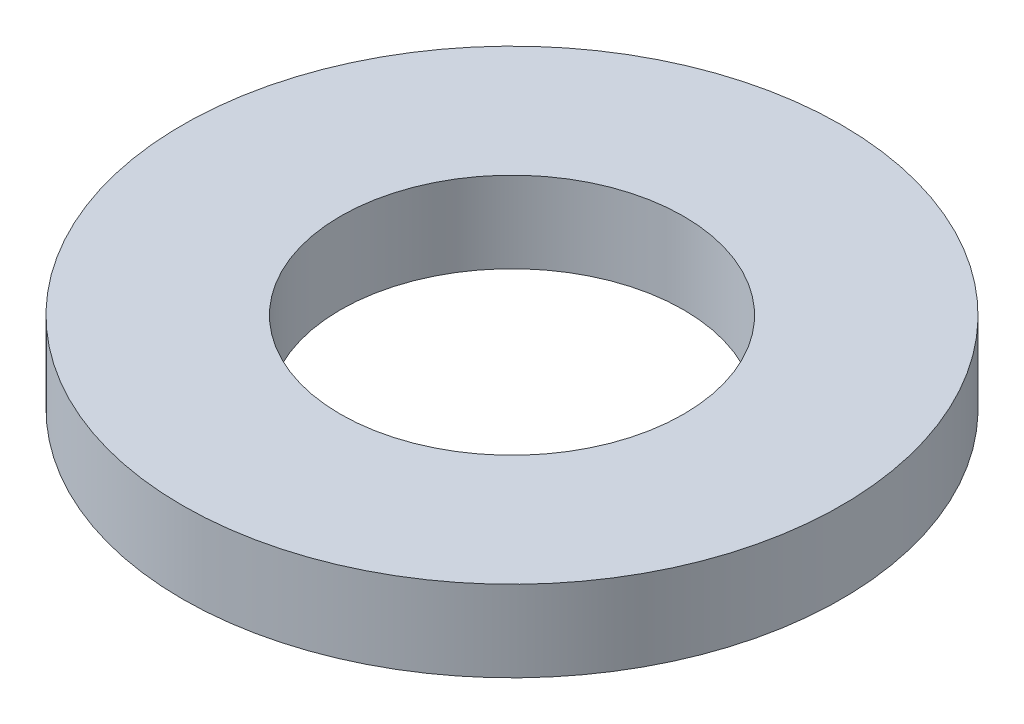
SolidWorks part; units mm, degrees
material "Alumina"
ref_plane "Front Plane" through (0, 0, 0) normal (0, 0, 1) x (1, 0, 0)
ref_plane "Top Plane" through (0, 0, 0) normal (0, 1, 0) x (1, 0, 0)
ref_plane "Right Plane" through (0, 0, 0) normal (1, 0, 0) x (0, 0, -1)
sketch "Sketch1" plane through (0, 0, 0) normal (0, 1, 0) x (1, 0, 0)
  circle A0 centre (0, 0) radius 12.2
  circle A1 centre (0, 0) radius 6.35
  dimension "D1" = 24.4
  dimension "D2" = 12.7
extrude "Boss-Extrude1" add sketch "Sketch1" along normal blind 3
